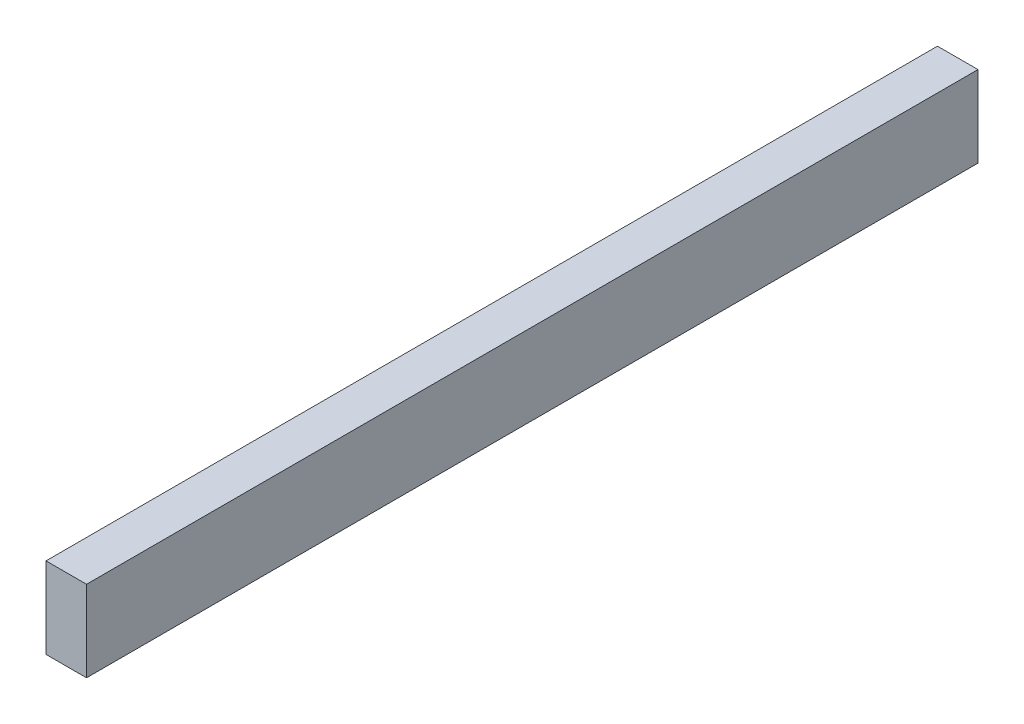
SolidWorks part; units mm, degrees
ref_plane "Front Plane" through (0, 0, 0) normal (0, 0, 1) x (1, 0, 0)
ref_plane "Top Plane" through (0, 0, 0) normal (0, 1, 0) x (1, 0, 0)
ref_plane "Right Plane" through (0, 0, 0) normal (1, 0, 0) x (0, 0, -1)
sketch "Sketch1" plane through (0, 0, 0) normal (0, 1, 0) x (1, 0, 0)
  line L1 (-12.7, 279.4) -> (12.7, 279.4)
  line L2 (-12.7, 279.4) -> (-12.7, -279.4)
  line L3 (-12.7, -279.4) -> (12.7, -279.4)
  line L4 (12.7, 279.4) -> (12.7, -279.4)
  line L5 (-12.7, 279.4) -> (12.7, -279.4) construction
  line L6 (-12.7, -279.4) -> (12.7, 279.4) construction
  point P0 (0, 0)
extrude "Boss-Extrude1" add sketch "Sketch1" along normal blind 50.8
